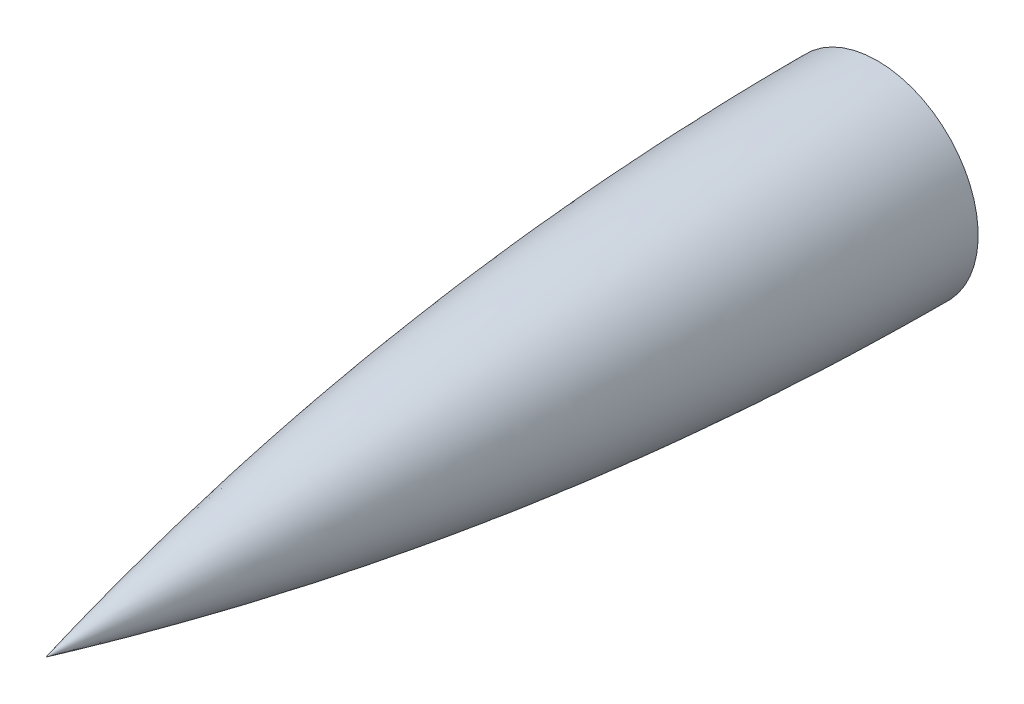
SolidWorks part; units mm, degrees
ref_plane "Front Plane" through (0, 0, 0) normal (0, 0, 1) x (1, 0, 0)
ref_plane "Top Plane" through (0, 0, 0) normal (0, 1, 0) x (1, 0, 0)
ref_plane "Right Plane" through (0, 0, 0) normal (1, 0, 0) x (0, 0, -1)
sketch "Sketch1" plane through (0, 0, 0) normal (1, 0, 0) x (0, 0, -1)
  line L0 (0, 50.8) -> (0, 0)
  line L1 (0, 0) -> (-419.1, 0)
  spline S0 degree 4 poles (-459.753, -10.5198) (-458.8979, -10.2876) (-457.188, -9.8245) (-454.6259, -9.1341) (-451.1978, -8.2181) (-446.9606, -7.0946) (-442.7021, -5.9783) (-438.5157, -4.8918) (-434.2469, -3.7972) (-430.9886, -2.9671) (-427.3742, -2.0565) (-424.5079, -1.3371) (-420.2908, -0.2927) (-418.3417, 0.1872) (-415.2679, 0.939) (-413.1135, 1.4623) (-411.0374, 1.964) (-408.2622, 2.6314) (-404.3783, 3.5579) (-400.1738, 4.5483) (-395.9226, 5.5377) (-391.6512, 6.5217) (-387.341, 7.5045) (-382.3125, 8.6363) (-375.1216, 10.2294) (-366.485, 12.1023) (-357.8374, 13.9269) (-349.1801, 15.7031) (-341.959, 17.1509) (-336.1783, 18.2897) (-330.3938, 19.4091) (-324.6056, 20.5091) (-317.3658, 21.8597) (-305.7724, 23.9689) (-269.4922, 30.276) (-211.1797, 38.8064) (-152.5404, 44.8505) (-95.1967, 48.4336) (-62.816, 49.6937) (-52.5106, 50.0254) (-43.676, 50.2603) (-37.7858, 50.3971) (-32.6315, 50.4995) (-28.2133, 50.5749) (-24.5472, 50.6293) (-21.6333, 50.6676) (-18.7349, 50.7009) (-15.8532, 50.7294) (-12.9736, 50.753) (-10.0727, 50.772) (-7.2352, 50.7862) (-4.3734, 50.7957) (-0.7824, 50.8006) (1.2225, 50.8003) (5.5599, 50.7937) (8.5094, 50.78) (12.2323, 50.7594) (15.5816, 50.7319) (19.1128, 50.6975) (22.5547, 50.6563) (26.0564, 50.608) (29.5522, 50.5525) (33.0747, 50.4897) (36.6075, 50.4195) (39.2594, 50.3614) (41.0265, 50.3204) (41.9099, 50.2993) knots 0 0 0 0 0 0.006985 0.01397 0.020955 0.02794 0.041657 0.048516 0.055375 0.062233 0.069092 0.075951 0.08281 0.088494 0.094178 0.09702 0.099862 0.105546 0.116914 0.128282 0.134092 0.139901 0.151519 0.163138 0.174757 0.197994 0.221231 0.23285 0.244468 0.256087 0.267706 0.279324 0.290943 0.31418 0.360654 0.569789 0.755687 0.778924 0.81378 0.825399 0.837017 0.848636 0.860254 0.866064 0.871873 0.877557 0.883241 0.888925 0.894609 0.900293 0.905978 0.911662 0.917346 0.924192 0.931037 0.937883 0.944729 0.951575 0.958421 0.965267 0.972113 0.979084 0.986056 0.993028 1 1 1 1 1 construction
  spline S1 degree 4 poles (-419.1, 0) (-418.516, 0.1437) (-417.3411, 0.432) (-415.2679, 0.939) (-413.1135, 1.4623) (-411.0374, 1.964) (-408.2622, 2.6314) (-404.3783, 3.5579) (-400.1738, 4.5483) (-395.9226, 5.5377) (-391.6512, 6.5217) (-387.341, 7.5045) (-382.3125, 8.6363) (-375.1216, 10.2294) (-366.485, 12.1023) (-357.8374, 13.9269) (-349.1801, 15.7031) (-341.959, 17.1509) (-336.1783, 18.2897) (-330.3938, 19.4091) (-324.6056, 20.5091) (-317.3658, 21.8597) (-305.7724, 23.9689) (-269.4922, 30.276) (-211.1797, 38.8064) (-152.5404, 44.8505) (-95.1967, 48.4336) (-62.816, 49.6937) (-52.5106, 50.0254) (-43.676, 50.2603) (-37.7858, 50.3971) (-32.6315, 50.4995) (-28.2133, 50.5749) (-24.5472, 50.6293) (-21.6333, 50.6676) (-18.7349, 50.7009) (-15.8532, 50.7294) (-12.9736, 50.753) (-10.0727, 50.772) (-7.2352, 50.7862) (-4.3734, 50.7957) (-1.8111, 50.7992) (-0.6014, 50.8) (0, 50.8) knots 0.08281 0.08281 0.08281 0.08281 0.08281 0.088494 0.094178 0.09702 0.099862 0.105546 0.116914 0.128282 0.134092 0.139901 0.151519 0.163138 0.174757 0.197994 0.221231 0.23285 0.244468 0.256087 0.267706 0.279324 0.290943 0.31418 0.360654 0.569789 0.755687 0.778924 0.81378 0.825399 0.837017 0.848636 0.860254 0.866064 0.871873 0.877557 0.883241 0.888925 0.894609 0.900293 0.905978 0.911662 0.917346 0.917346 0.917346 0.917346 0.917346
  dimension "D1" = 50.8
revolve "Revolve1" add sketch "Sketch1" angle 360 about L1
equation "\"R\"= 2'base radius"
equation "\"L\"= 16.5'overall length"
equation "\"rho\"= ( \"R\" ^ 2 + \"L\" ^ 2 ) / ( 2 * \"R\" )'ogive radius"
equation "\"D1@Sketch1\"=\"R\""
